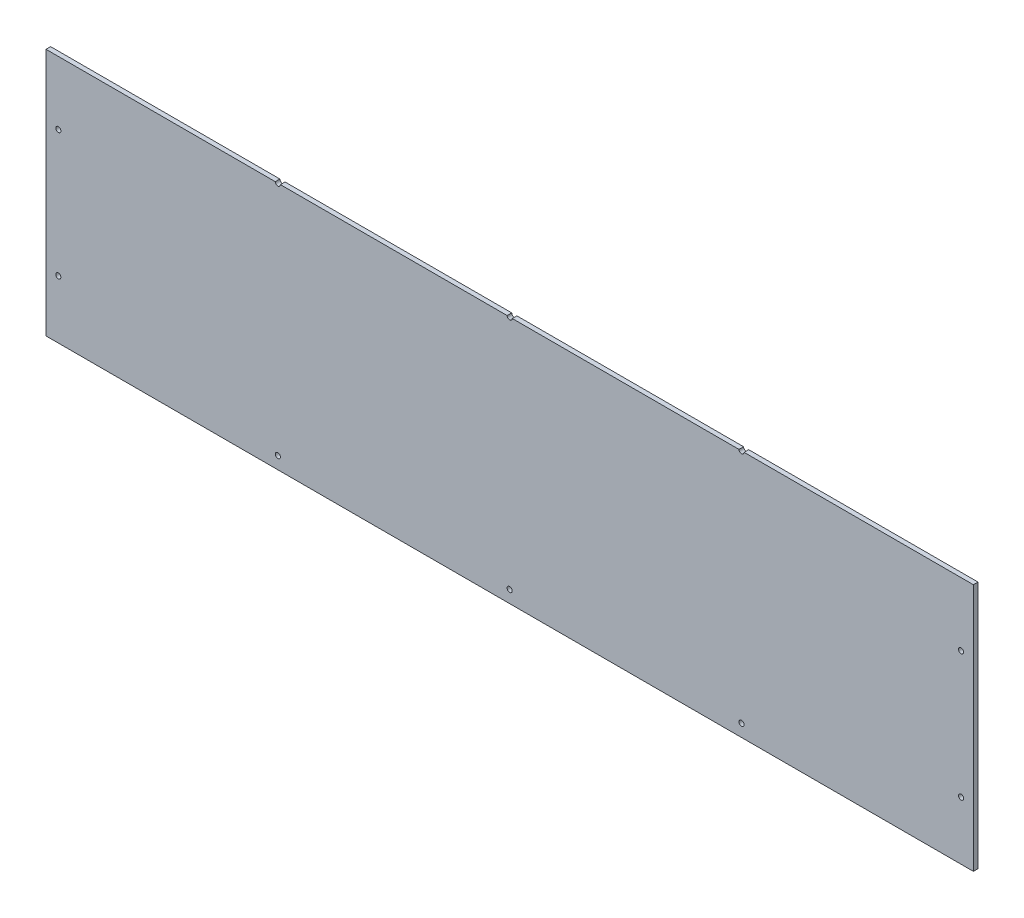
SolidWorks part; units mm, degrees
ref_plane "Front Plane" through (0, 0, 0) normal (0, 0, 1) x (1, 0, 0)
ref_plane "Top Plane" through (0, 0, 0) normal (0, 1, 0) x (1, 0, 0)
ref_plane "Right Plane" through (0, 0, 0) normal (1, 0, 0) x (0, 0, -1)
sketch "Sketch1" plane through (0, 0, 0) normal (0, 0, 1) x (1, 0, 0)
  line L2 (-452, 123.5) -> (-452, -118.5)
  line L4 (452, 123.5) -> (452, -118.5)
  line L10 (-452, -118.5) -> (452, -118.5)
  line L11 (0, -118.5) -> (0, 123.5) construction
  line L16 (-452, 2.5) -> (452, 2.5) construction
  line L25 (-452, 123.5) -> (-228.5, 123.5)
  line L26 (-223.5, 123.5) -> (-2.5, 123.5)
  line L27 (228.5, 123.5) -> (452, 123.5)
  line L28 (2.5, 123.5) -> (223.5, 123.5)
  arc A3 (-2.5, 123.5) -> (2.5, 123.5) centre (0, 123.5) ccw
  circle A8 centre (-440, 61.75) radius 2.5
  circle A9 centre (-440, -61.75) radius 2.5
  circle A10 centre (440, -61.75) radius 2.5
  circle A12 centre (440, 61.75) radius 2.5
  circle A15 centre (0, -106.5) radius 2.5
  circle A27 centre (226, -106.5) radius 2.5
  circle A28 centre (-226, -106.5) radius 2.5
  arc A29 (223.5, 123.5) -> (228.5, 123.5) centre (226, 123.5) ccw
  arc A30 (-228.5, 123.5) -> (-223.5, 123.5) centre (-226, 123.5) ccw
  point P18 (-452, 123.5)
  dimension "D5" = 2
  dimension "D3" = 5
  dimension "D7" = 12
  dimension "D1" = 242
  dimension "D2" = 904
  dimension "D4" = 452
  dimension "D8" = 12
  dimension "D9" = 12
  dimension "D6" = 2
extrude "Boss-Extrude1" add sketch "Sketch1" along normal blind 4.5
